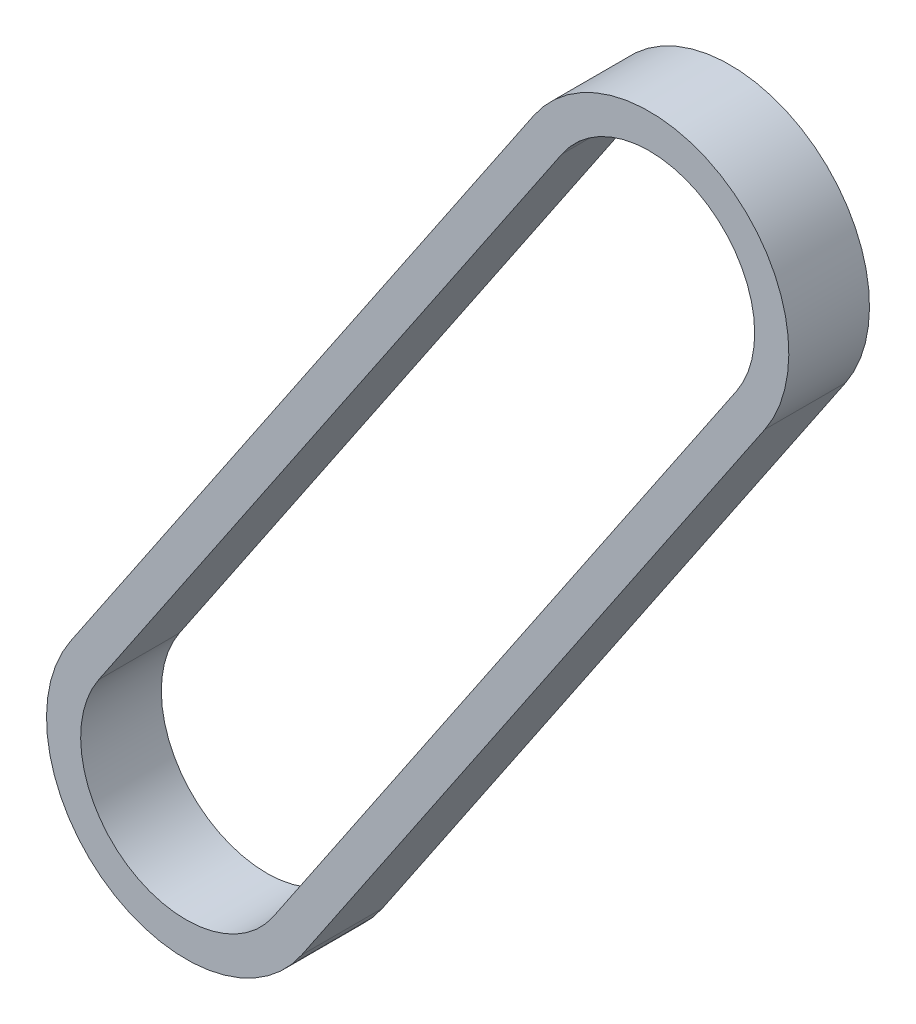
SolidWorks part; units mm, degrees
ref_plane "Front Plane" through (0, 0, 0) normal (0, 0, 1) x (1, 0, 0)
ref_plane "Top Plane" through (0, 0, 0) normal (0, 1, 0) x (1, 0, 0)
ref_plane "Right Plane" through (0, 0, 0) normal (1, 0, 0) x (0, 0, -1)
sketch "Sketch2" plane through (0, 0, 0) normal (0, 0, 1) x (1, 0, 0)
  line L0 (0, 0) -> (1, 0) construction
  line L1 (0, 0) -> (0, 1) construction
  line L2 (-11.4682, 7.7354) -> (40.2217, 84.3687)
  line L3 (63.158, 68.898) -> (11.4682, -7.7354)
  arc A0 (11.4682, -7.7354) -> (-11.4682, 7.7354) centre (0, 0) cw
  arc A1 (40.2217, 84.3687) -> (63.158, 68.898) centre (51.6898, 76.6333) cw
extrude "Extrude-Thin1" add sketch "Sketch2" along normal blind 9 thin thin type two direction wall 1.73 second wall 2.08
